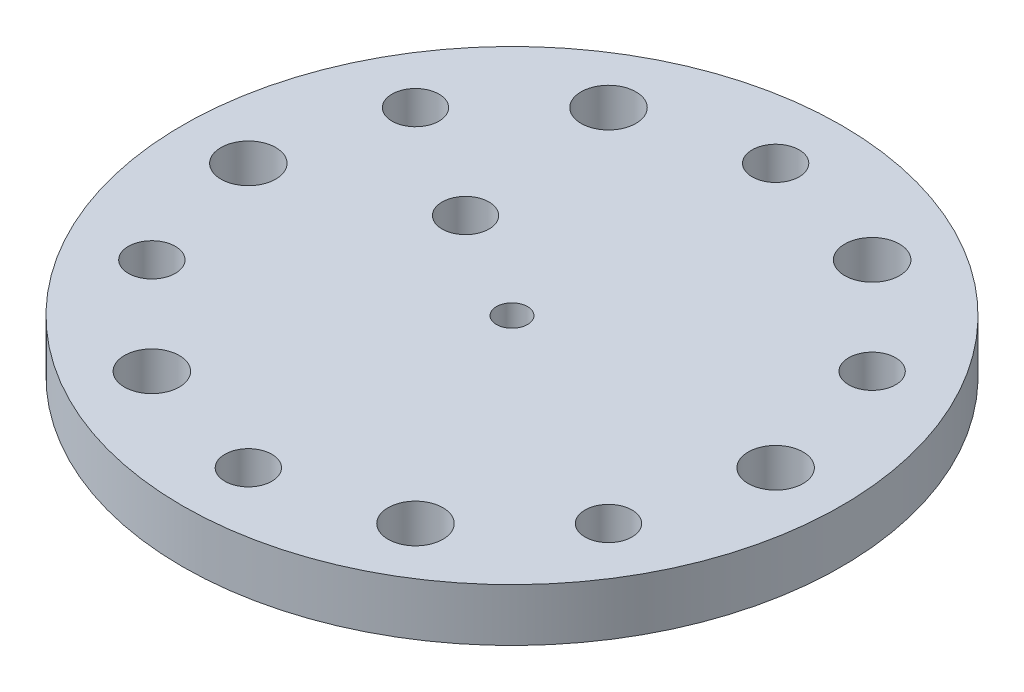
SolidWorks part; units mm, degrees
ref_plane "Front Plane" through (0, 0, 0) normal (0, 0, 1) x (1, 0, 0)
ref_plane "Top Plane" through (0, 0, 0) normal (0, 1, 0) x (1, 0, 0)
ref_plane "Right Plane" through (0, 0, 0) normal (1, 0, 0) x (0, 0, -1)
sketch "Sketch1" plane through (0, 0, 0) normal (0, 1, 0) x (1, 0, 0)
  circle A0 centre (0, 0) radius 15.875
extrude "Boss-Extrude1" add sketch "Sketch1" along normal blind 2.54
sketch "Sketch2" plane through (0, 2.54, 0) normal (0, 1, 0) x (1, 0, 0)
  circle A3 centre (0, 12.7) radius 1.5875
sketch "Sketch3" plane through (0, 2.54, 0) normal (0, 1, 0) x (1, 0, 0)
  line L1 (8.2489, -4.7625) -> (8.2489, 4.7625)
  line L2 (8.2489, 4.7625) -> (0, 9.525)
  line L3 (0, 9.525) -> (-8.2489, 4.7625)
  line L4 (-8.2489, 4.7625) -> (-8.2489, -4.7625)
  line L5 (-8.2489, -4.7625) -> (0, -9.525)
  line L6 (0, -9.525) -> (8.2489, -4.7625)
  circle A0 centre (0, 0) radius 8.2489 construction
hole_wizard "Tap Drill for #4-40 Tap1" positions "Sketch7" profile "Sketch6" hole size "#4-40" standard "ANSI Inch" end condition through all
sketch "Sketch7" plane through (0, 2.54, 0) normal (0, 1, 0) x (1, 0, 0)
  point P0 (0, 12.7)
sketch "Sketch6" plane through (0, 2.54, -12.7) normal (1, 0, 0) x (0, 0, 1)
  line L0 (0, 0) -> (0, 2.54)
  line L1 (0, 2.54) -> (1.1303, 2.54)
  line L2 (1.1303, 2.54) -> (1.1303, 0)
  line L5 (1.1303, 0) -> (0, 0)
  line L11 (0, -6.35) -> (0, 107.95) construction
  dimension "Thru Hole Dia." = 2.2606
  dimension "Thru Hole Depth" = 2.54
pattern_circular "CirPattern1" count 6 every 60 about axis through (0, 0, 0) along (0, 1, 0) of "Tap Drill for #4-40 Tap1"
sketch "Sketch8" plane through (0, 2.54, 0) normal (0, 1, 0) x (1, 0, 0)
  circle A0 centre (0, 0) radius 0.7493
extrude "Cut-Extrude1" cut sketch "Sketch8" against normal blind 2.54
sketch "Sketch15" plane through (0, 2.54, 0) normal (0, 1, 0) x (1, 0, 0)
  circle A0 centre (12.7, 0) radius 1.3208
extrude "Cut-Extrude2" cut sketch "Sketch15" against normal blind 2.54
pattern_circular "CirPattern2" count 6 every 60 about axis through (0, 0, 0) along (0, 1, 0) of "Cut-Extrude2"
sketch "Sketch18" plane through (0, 2.54, 0) normal (0, 1, 0) x (1, 0, 0)
  line L0 (0, 0) -> (5.2914, -3.055)
  line L1 (0, 0) -> (-5.2914, 3.055)
hole_wizard "#4-40 Tapped Hole3" positions "Sketch22" profile "Sketch21" tap size "#4-40" standard "ANSI Inch" end condition through all
sketch "Sketch22" plane through (0, 2.54, 0) normal (0, 1, 0) x (1, 0, 0)
  point P0 (-5.2914, 3.055)
sketch "Sketch21" plane through (-5.2914, 2.54, -3.055) normal (1, 0, 0) x (0, 0, 1)
  line L0 (0, 0) -> (0, 2.54)
  line L1 (0, 2.54) -> (1.1303, 2.54)
  line L2 (1.1303, 2.54) -> (1.1303, 0)
  line L5 (1.1303, 0) -> (0, 0)
  line L11 (0, -6.35) -> (0, 107.95) construction
  dimension "Thru Tap Drill Dia." = 2.2606
  dimension "Thru Tap Drill Depth" = 2.54
cosmetic thread "Hole Thread4" parameters "D2"=2.8448
